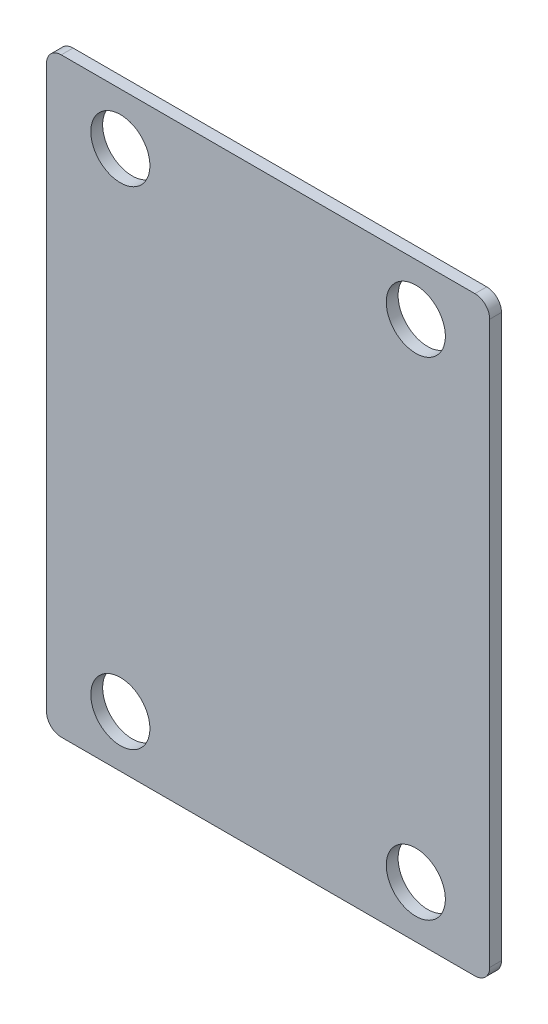
SolidWorks part; units mm, degrees
ref_plane "前视基准面" through (0, 0, 0) normal (0, 0, 1) x (1, 0, 0)
ref_plane "上视基准面" through (0, 0, 0) normal (0, 1, 0) x (1, 0, 0)
ref_plane "右视基准面" through (0, 0, 0) normal (1, 0, 0) x (0, 0, -1)
sketch "草图1" plane through (0, 0, 0) normal (0, 0, 1) x (1, 0, 0)
  line L0 (0, 40) -> (0, 9.672) construction
  line L1 (-30, -40) -> (30, -40)
  line L2 (-30, -40) -> (-30, 40)
  line L3 (-30, 40) -> (30, 40)
  line L4 (30, -40) -> (30, 40)
  line L5 (-30, -40) -> (30, 40) construction
  line L6 (-30, 40) -> (30, -40) construction
  line L7 (30, 0) -> (0, 0) construction
  circle A0 centre (-20, 33) radius 4
  circle A1 centre (20, 33) radius 4
  circle A2 centre (20, -33) radius 4
  circle A3 centre (-20, -33) radius 4
  point P0 (0, 0)
  dimension "D3" = 8
  dimension "D1" = 80
  dimension "D2" = 60
  dimension "D4" = 7
  dimension "D5" = 10
extrude "凸台-拉伸1" add sketch "草图1" along normal blind 1.6
fillet "圆角1" radius 2 4 edges at (-30, -40, 0.8) (-30, 40, 0.8) (30, -40, 0.8) (30, 40, 0.8)
